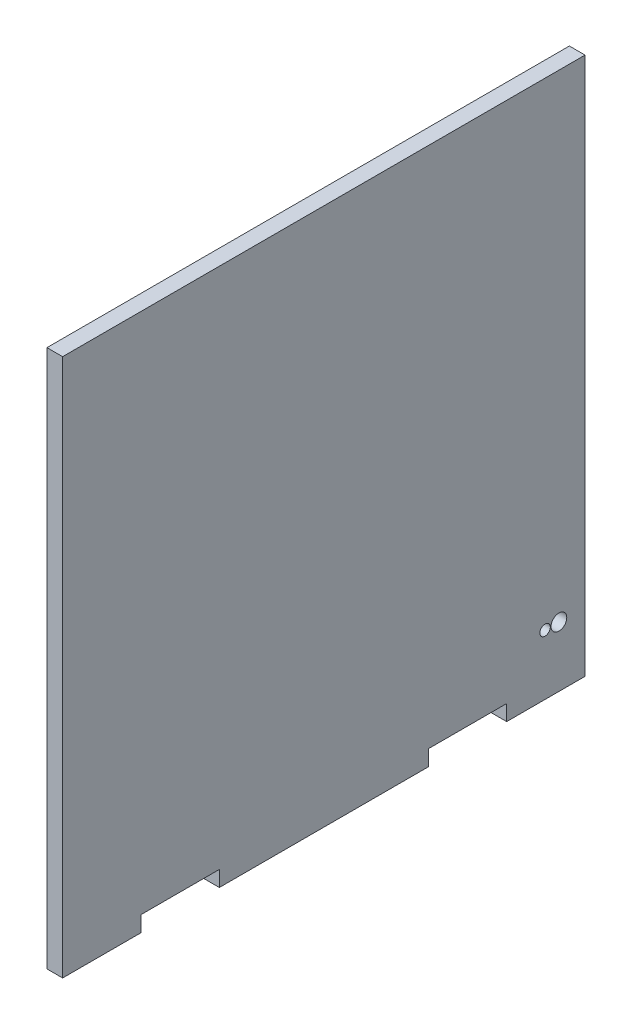
SolidWorks part; units mm, degrees
ref_plane "Plano frontal" through (0, 0, 0) normal (0, 0, 1) x (1, 0, 0)
ref_plane "Plano superior" through (0, 0, 0) normal (0, 1, 0) x (1, 0, 0)
ref_plane "Plano direito" through (0, 0, 0) normal (1, 0, 0) x (0, 0, -1)
sketch "Esboço1" plane through (0, 0, 0) normal (1, 0, 0) x (0, 0, -1)
  line L0 (-70, -103) -> (-100, -103)
  line L2 (-100, -103) -> (-100, 103)
  line L3 (-100, 103) -> (100, 103)
  line L4 (100, -103) -> (100, 103)
  line L5 (-100, -103) -> (100, 103) construction
  line L6 (-100, 103) -> (100, -103) construction
  line L8 (-70, -103) -> (-70, -97)
  line L9 (-70, -97) -> (-40, -97)
  line L10 (-40, -103) -> (-40, -97)
  line L12 (40, -103) -> (40, -97)
  line L13 (40, -97) -> (70, -97)
  line L14 (70, -103) -> (70, -97)
  line L15 (-40, -103) -> (40, -103)
  line L16 (70, -103) -> (100, -103)
  point P0 (0, 0)
  dimension "D1" = 200
  dimension "D2" = 206
  dimension "D3" = 30
  dimension "D4" = 30
  dimension "D5" = 30
  dimension "D6" = 30
  dimension "D7" = 6
  dimension "D8" = 6
  dimension "D9" = 6
  dimension "D10" = 6
extrude "Ressalto-extrusão3" add sketch "Esboço1" along normal blind 6 contours L13 L14 L16 L4 L3 L2 L0 L8 L9 L10 L15 L12
sketch "Esboço3" plane through (6, 0, 0) normal (1, 0, 0) x (0, 0, -1)
  line L0 (40, -97) -> (70, -97) construction
  line L1 (100, -103) -> (100, 103) construction
  circle A0 centre (90, -80) radius 3
  circle A1 centre (84.7, -80) radius 2
  dimension "D1" = 4
  dimension "D2" = 6
  dimension "D3" = 17
  dimension "D4" = 17
  dimension "D5" = 5.3
  dimension "D6" = 10
extrude "Corte-extrusão4" cut sketch "Esboço3" against normal blind 6 contours A0 | A1
